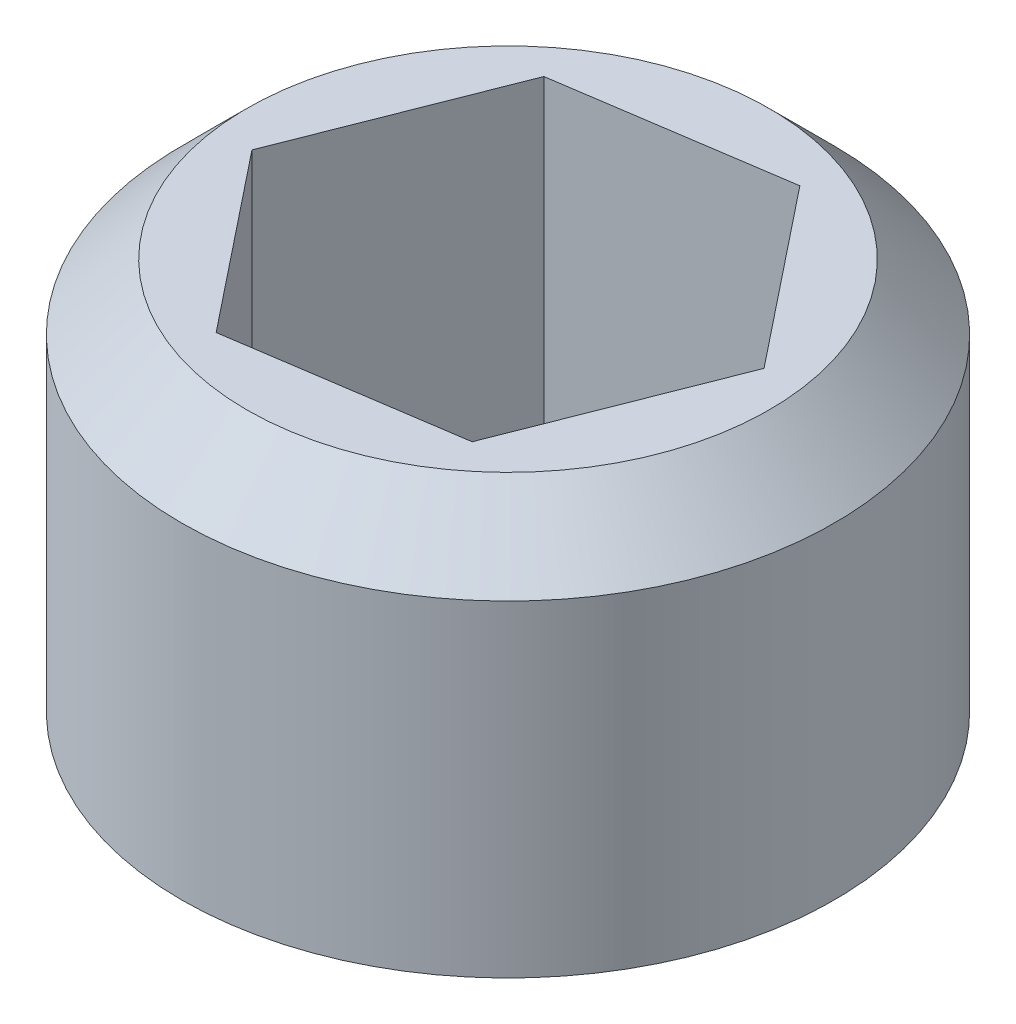
SolidWorks part; units mm, degrees
ref_plane "前视基准面" through (0, 0, 0) normal (0, 0, 1) x (1, 0, 0)
ref_plane "上视基准面" through (0, 0, 0) normal (0, 1, 0) x (1, 0, 0)
ref_plane "右视基准面" through (0, 0, 0) normal (1, 0, 0) x (0, 0, -1)
sketch "草图1" plane through (0, 0, 0) normal (0, 1, 0) x (1, 0, 0)
  circle A0 centre (0, 0) radius 5
  dimension "D1" = 10
extrude "凸台-拉伸1" add sketch "草图1" along normal blind 6
sketch "草图2" plane through (0, 6, 0) normal (0, 1, 0) x (1, 0, 0)
  line L1 (1.2615, 3.2087) -> (-2.148, 2.6969)
  line L2 (-2.148, 2.6969) -> (-3.4096, -0.5118)
  line L3 (-3.4096, -0.5118) -> (-1.2615, -3.2087)
  line L4 (-1.2615, -3.2087) -> (2.148, -2.6969)
  line L5 (2.148, -2.6969) -> (3.4096, 0.5118)
  line L6 (3.4096, 0.5118) -> (1.2615, 3.2087)
  circle A0 centre (0, 0) radius 2.9859 construction
extrude "切除-拉伸1" cut sketch "草图2" against normal blind 5
chamfer "倒角1" distance 1 angle 45 1 edges at (0, 6, 5)
